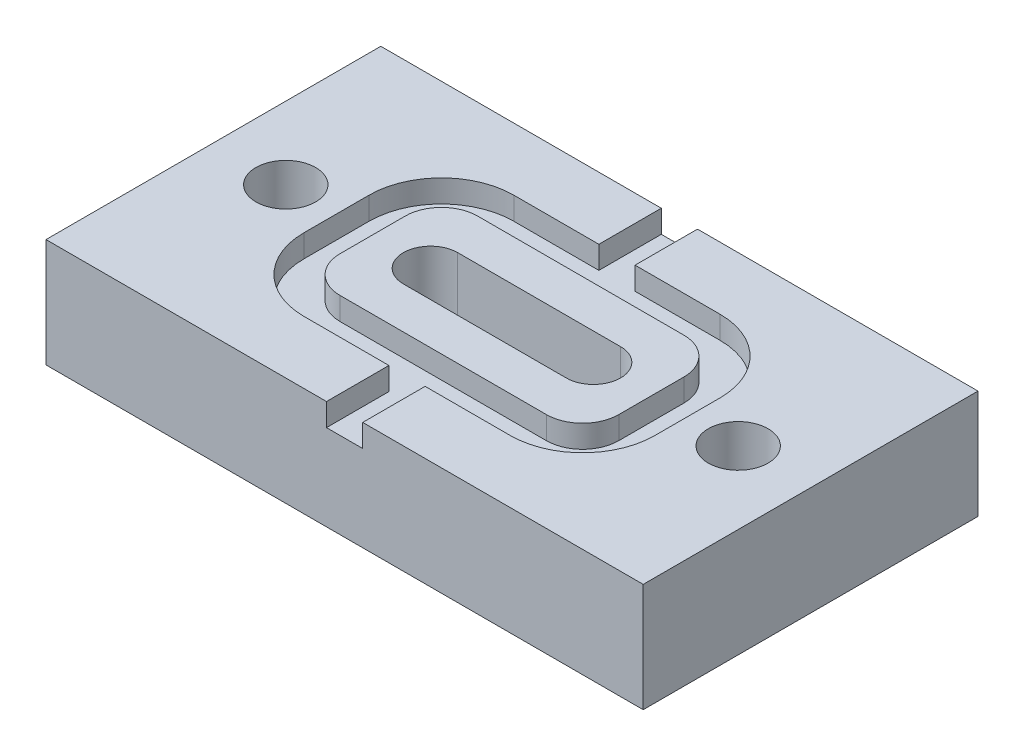
SolidWorks part; units mm, degrees
ref_plane "Front Plane" through (0, 0, 0) normal (0, 0, 1) x (1, 0, 0)
ref_plane "Top Plane" through (0, 0, 0) normal (0, 1, 0) x (1, 0, 0)
ref_plane "Right Plane" through (0, 0, 0) normal (1, 0, 0) x (0, 0, -1)
sketch "Sketch2" plane through (0, 0, 0) normal (0, 1, 0) x (1, 0, 0)
  line L1 (-16.5, -9.25) -> (16.5, -9.25)
  line L2 (-16.5, -9.25) -> (-16.5, 9.25)
  line L3 (-16.5, 9.25) -> (16.5, 9.25)
  line L4 (16.5, -9.25) -> (16.5, 9.25)
  line L5 (-16.5, -9.25) -> (16.5, 9.25) construction
  line L6 (-16.5, 9.25) -> (16.5, -9.25) construction
  point P0 (0, 0)
  point P6 (0, 0)
  dimension "D1" = 33
  dimension "D2" = 18.5
extrude "Boss-Extrude1" add sketch "Sketch2" along normal blind 6
sketch "Sketch3" plane through (0, 6, 0) normal (0, 1, 0) x (1, 0, 0)
  line L0 (-1, 9.25) -> (1, 9.25)
  line L1 (-5.7, -3.8) -> (5.7, -3.8)
  line L2 (-7.7, -1.8) -> (-7.7, 1.8)
  line L3 (-5.7, 3.8) -> (5.7, 3.8)
  line L4 (7.7, -1.8) -> (7.7, 1.8)
  line L5 (-7.7, -3.8) -> (7.7, 3.8) construction
  line L6 (-7.7, 3.8) -> (7.7, -3.8) construction
  line L8 (-9.7, -1.8) -> (-9.7, 1.8)
  line L10 (9.7, -1.8) -> (9.7, 1.8)
  line L11 (-9.7, -5.8) -> (9.7, 5.8) construction
  line L12 (-9.7, 5.8) -> (9.7, -5.8) construction
  line L13 (-5.7, 5.8) -> (-1, 5.8)
  line L14 (1, 5.8) -> (1, 9.25)
  line L15 (-1, 5.8) -> (-1, 9.25)
  line L16 (5.7, 5.8) -> (1, 5.8)
  line L17 (-1, -9.25) -> (1, -9.25)
  line L19 (-1, -5.8) -> (-1, -9.25)
  line L20 (1, -5.8) -> (1, -9.25)
  line L21 (-5.7, -5.8) -> (-1, -5.8)
  line L22 (5.7, -5.8) -> (1, -5.8)
  arc A0 (5.7, 3.8) -> (7.7, 1.8) centre (5.7, 1.8) cw
  arc A1 (5.7, -3.8) -> (7.7, -1.8) centre (5.7, -1.8) ccw
  arc A2 (-5.7, -3.8) -> (-7.7, -1.8) centre (-5.7, -1.8) cw
  arc A3 (-7.7, 1.8) -> (-5.7, 3.8) centre (-5.7, 1.8) cw
  arc A4 (5.7, 5.8) -> (9.7, 1.8) centre (5.7, 1.8) cw
  arc A5 (5.7, -5.8) -> (9.7, -1.8) centre (5.7, -1.8) ccw
  arc A6 (-5.7, -5.8) -> (-9.7, -1.8) centre (-5.7, -1.8) cw
  arc A7 (-9.7, 1.8) -> (-5.7, 5.8) centre (-5.7, 1.8) cw
  point P0 (0, 0)
  point P6 (0, 0)
  dimension "D5" = 2
  dimension "D6" = 4
  dimension "D1" = 15.4
  dimension "D2" = 19.4
  dimension "D3" = 7.6
  dimension "D4" = 11.6
extrude "Cut-Extrude1" cut sketch "Sketch3" against normal blind 1.25
sketch "Sketch4" plane through (0, 6, 0) normal (0, 1, 0) x (1, 0, 0)
  circle A0 centre (-12.5, 0) radius 1.65
  circle A1 centre (12.5, 0) radius 1.65
  dimension "D1" = 12.5
  dimension "D2" = 12.5
extrude "Cut-Extrude2" cut sketch "Sketch4" against normal through all
sketch "Sketch5" plane through (0, 6, 0) normal (0, 1, 0) x (1, 0, 0)
  line L1 (-4.5, -1.5) -> (4.5, -1.5)
  line L3 (-4.5, 1.5) -> (4.5, 1.5)
  line L5 (-4.5, -1.5) -> (4.5, 1.5) construction
  line L6 (-4.5, 1.5) -> (4.5, -1.5) construction
  arc A0 (-4.5, 1.5) -> (-4.5, -1.5) centre (-4.5, 0) ccw
  arc A1 (4.5, -1.5) -> (4.5, 1.5) centre (4.5, 0) ccw
  point P0 (0, 0)
  dimension "D1" = 9
  dimension "D2" = 3
extrude "Cut-Extrude3" cut sketch "Sketch5" against normal through all
